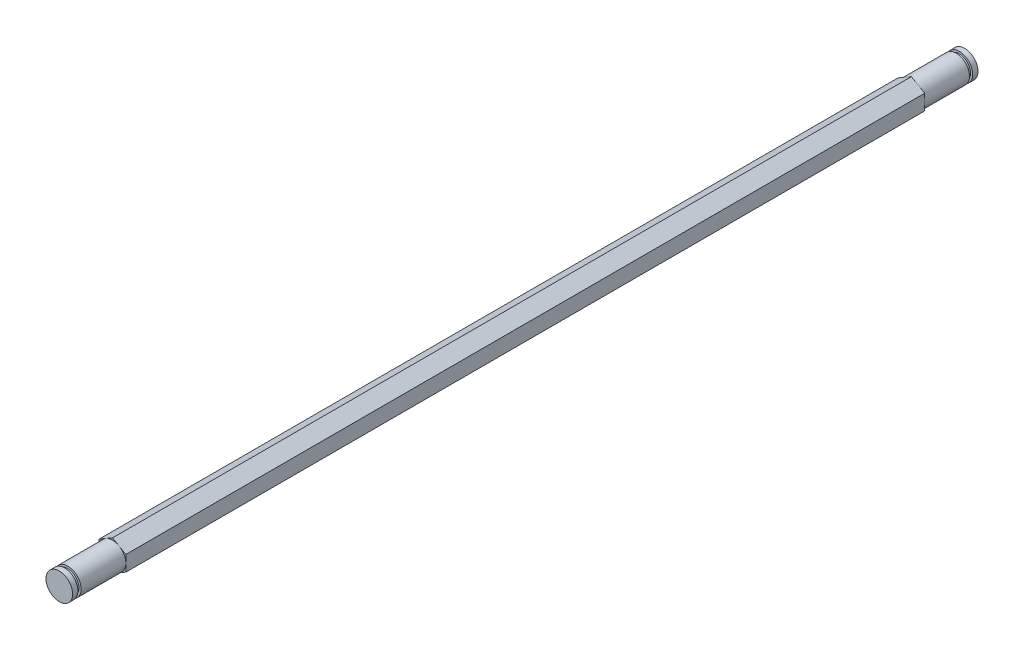
SolidWorks part; units mm, degrees
ref_plane "Front" through (0, 0, 0) normal (0, 0, 1) x (1, 0, 0)
ref_plane "Top" through (0, 0, 0) normal (0, 1, 0) x (1, 0, 0)
ref_plane "Right" through (0, 0, 0) normal (1, 0, 0) x (0, 0, -1)
sketch "Sketch1" plane through (0, 0, 0) normal (0, 0, 1) x (1, 0, 0)
  line L1 (0, 3.6662) -> (-3.175, 1.8331)
  line L2 (-3.175, 1.8331) -> (-3.175, -1.8331)
  line L3 (-3.175, -1.8331) -> (0, -3.6662)
  line L4 (0, -3.6662) -> (3.175, -1.8331)
  line L5 (3.175, -1.8331) -> (3.175, 1.8331)
  line L6 (3.175, 1.8331) -> (0, 3.6662)
  circle A0 centre (0, 0) radius 3.175 construction
  dimension "Width" = 6.35
sketch "Sketch2" plane through (0, 0, 0) normal (1, 0, 0) x (0, 0, -1)
  line L0 (-152.4, 0) -> (152.4, 0) construction
  line L1 (-101.6, 3.6662) -> (-101.6, -3.6662) construction
  line L2 (101.6, 3.6662) -> (101.6, -3.6662) construction
  line L3 (-152.4, 3.6662) -> (-152.4, -3.6662) construction
  line L4 (152.4, 3.6662) -> (152.4, -3.6662) construction
  point P2 (-101.6, 0)
  point P4 (101.6, 0)
  dimension "D1" = 50.8
  dimension "Length" = 304.8
  dimension "D2" = 50.8
sketch "Sketch3" plane through (0, 0, 0) normal (0, 0, 1) x (1, 0, 0)
  line L0 (0, 3.6662) -> (-3.175, 1.8331) construction
  line L1 (-3.175, 1.8331) -> (-3.175, -1.8331) construction
  line L2 (-3.175, -1.8331) -> (0, -3.6662) construction
  line L3 (0, -3.6662) -> (3.175, -1.8331) construction
  line L4 (3.175, -1.8331) -> (3.175, 1.8331) construction
  line L5 (3.175, 1.8331) -> (0, 3.6662) construction
  line L6 (0, 3.6662) -> (-3.175, 1.8331)
  line L7 (-3.175, 1.8331) -> (-3.175, -1.8331)
  line L8 (-3.175, -1.8331) -> (0, -3.6662)
  line L9 (0, -3.6662) -> (3.175, -1.8331)
  line L10 (3.175, -1.8331) -> (3.175, 1.8331)
  line L11 (3.175, 1.8331) -> (0, 3.6662)
extrude "Boss-Extrude2" add sketch "Sketch3" along normal blind 215.9
sketch "Sketch5" plane through (0, 0, 0) normal (0, 0, -1) x (-1, 0, 0)
  circle A0 centre (0, 0) radius 3.175
  dimension "D1" = 6.35
extrude "Cut-Extrude1" cut sketch "Sketch5" against normal blind 12.7 flip side to cut
sketch "Sketch6" plane through (0, 0, 215.9) normal (0, 0, 1) x (1, 0, 0)
  circle A0 centre (0, 0) radius 3.175
  dimension "D1" = 6.35
extrude "Cut-Extrude2" cut sketch "Sketch6" against normal blind 12.7 flip side to cut
ref_plane "Plane1" through (0, 0, 214.63) normal (0, 0, 1) x (1, 0, 0)
sketch "Sketch7" plane through (0, 0, 214.63) normal (0, 0, 1) x (1, 0, 0)
  circle A0 centre (0, 0) radius 2.667
  dimension "D1" = 5.334
extrude "Cut-Extrude3" cut sketch "Sketch7" against normal blind 0.762 flip side to cut
ref_plane "Plane2" through (0, 0, 1.27) normal (0, 0, -1) x (-1, 0, 0)
sketch "Sketch9" plane through (0, 0, 1.27) normal (0, 0, -1) x (-1, 0, 0)
  circle A0 centre (0, 0) radius 2.667
  dimension "D1" = 5.334
extrude "Cut-Extrude4" cut sketch "Sketch9" against normal blind 0.762 flip side to cut
